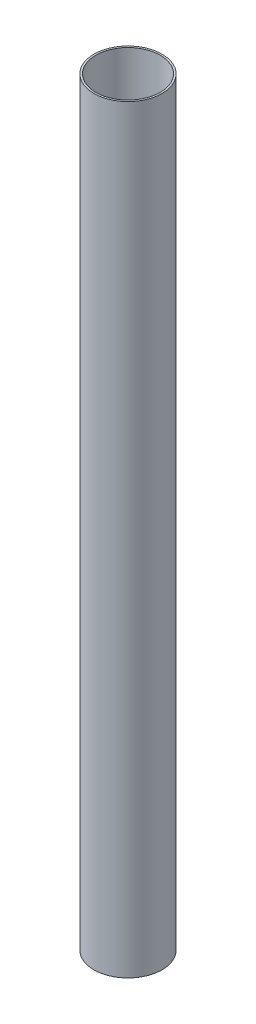
SolidWorks part; units mm, degrees
ref_plane "Front Plane" through (0, 0, 0) normal (0, 0, 1) x (1, 0, 0)
ref_plane "Top Plane" through (0, 0, 0) normal (0, 1, 0) x (1, 0, 0)
ref_plane "Right Plane" through (0, 0, 0) normal (1, 0, 0) x (0, 0, -1)
sketch "Sketch1" plane through (0, 0, 0) normal (0, 1, 0) x (1, 0, 0)
  circle A0 centre (0, 0) radius 25.1714
  circle A1 centre (0, 0) radius 23.8125
  dimension "D1" = 50.3428
  dimension "D2" = 47.625
extrude "Boss-Extrude1" add sketch "Sketch1" along normal blind 560.9336
